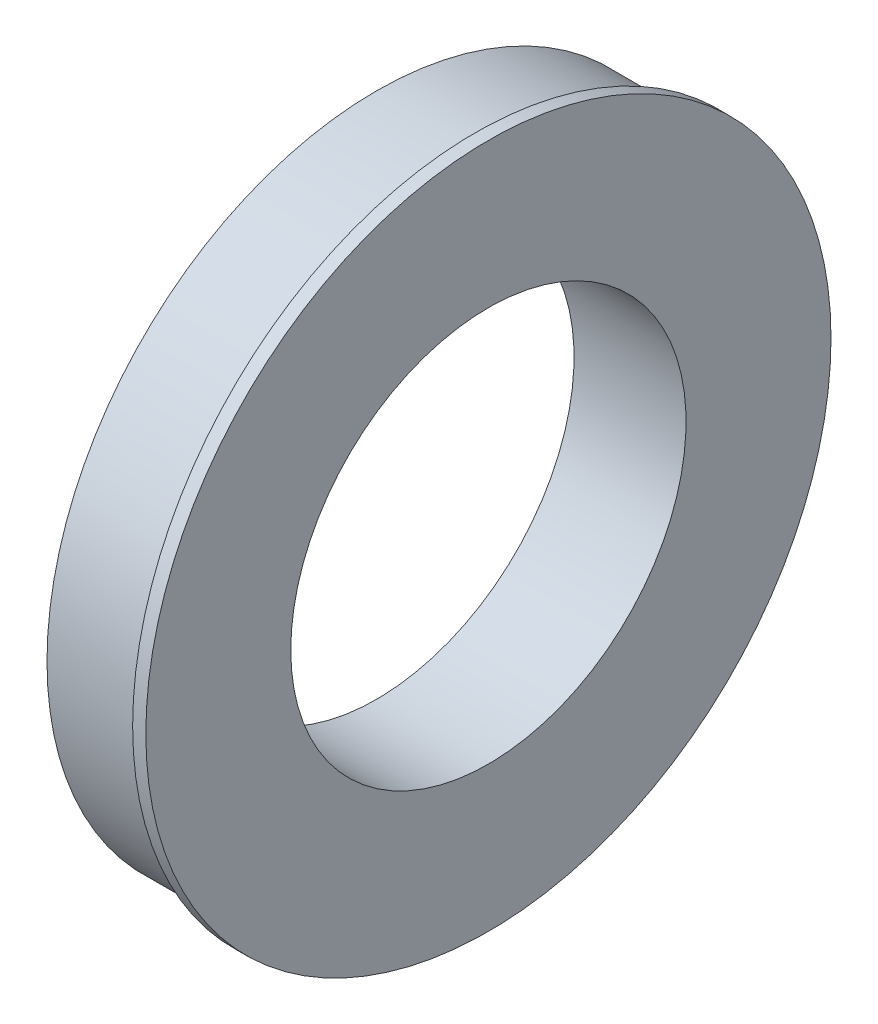
SolidWorks part; units mm, degrees
ref_plane "Front Plane" through (0, 0, 0) normal (0, 0, 1) x (1, 0, 0)
ref_plane "Top Plane" through (0, 0, 0) normal (0, 1, 0) x (1, 0, 0)
ref_plane "Right Plane" through (0, 0, 0) normal (1, 0, 0) x (0, 0, -1)
sketch "Sketch1" plane through (0, 0, 0) normal (1, 0, 0) x (0, 0, -1)
  circle A0 centre (0, 0) radius 38.1
  circle A1 centre (0, 0) radius 63.5
  dimension "D1" = 76.2
  dimension "D2" = 127
extrude "Boss-Extrude1" add sketch "Sketch1" along normal blind 19.05
sketch "Sketch2" plane through (19.05, 0, 0) normal (1, 0, 0) x (0, 0, -1)
  circle A1 centre (0, 0) radius 38.1 construction
  circle A2 centre (0, 0) radius 66.04
  circle A3 centre (0, 0) radius 66.04
  circle A4 centre (0, 0) radius 38.1
  dimension "D1" = 2.54
extrude "Boss-Extrude2" add sketch "Sketch2" along normal blind 2.54
scale "Scale1" scale about centroid uniform scaling yes scale factor 0.51948
